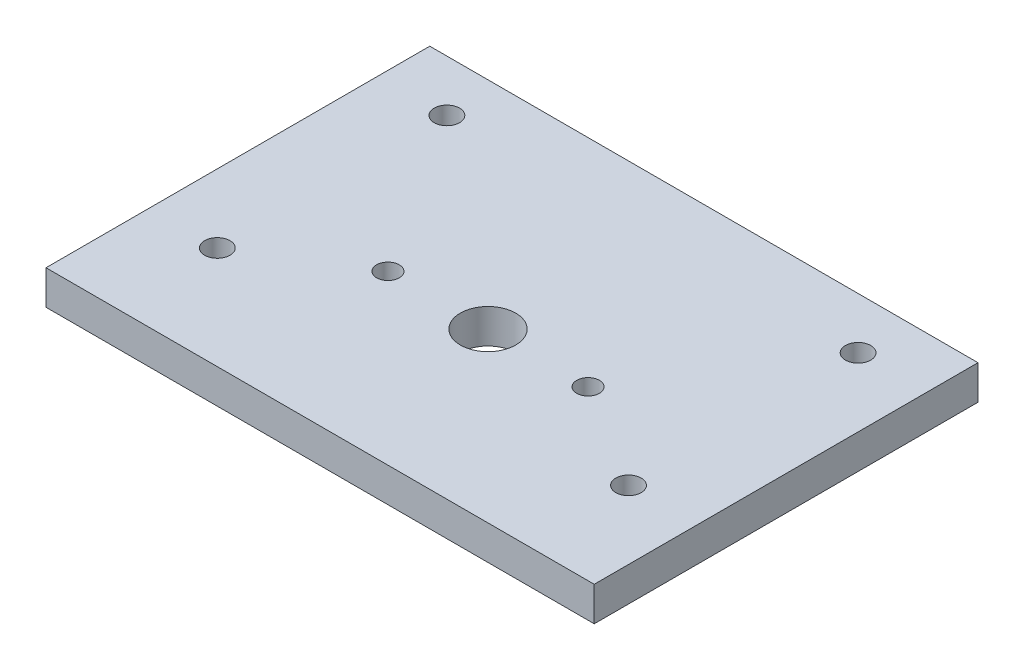
SolidWorks part; units mm, degrees
ref_plane "Front Plane" through (0, 0, 0) normal (0, 0, 1) x (1, 0, 0)
ref_plane "Top Plane" through (0, 0, 0) normal (0, 1, 0) x (1, 0, 0)
ref_plane "Right Plane" through (0, 0, 0) normal (1, 0, 0) x (0, 0, -1)
sketch "Sketch1" plane through (0, 0, 0) normal (0, 1, 0) x (1, 0, 0)
  line L1 (0, 0) -> (101.6, 0)
  line L2 (0, 0) -> (0, 71.12)
  line L3 (0, 71.12) -> (101.6, 71.12)
  line L4 (101.6, 0) -> (101.6, 71.12)
  dimension "D1" = 101.6
  dimension "D2" = 71.12
extrude "base" add sketch "Sketch1" along normal blind 6.35
hole_wizard "woodscrew clearance holes" positions "Sketch2" profile "Sketch3" hole size "#13" standard "ANSI Inch"
sketch "Sketch2" plane through (0, 6.35, 0) normal (0, 1, 0) x (1, 0, 0)
  line L2 (12.7, 61.595) -> (88.9, 61.595)
  line L3 (12.7, 61.595) -> (12.7, 19.05)
  line L4 (12.7, 19.05) -> (88.9, 19.05)
  line L5 (88.9, 61.595) -> (88.9, 19.05)
  line L6 (101.6, 71.12) -> (0, 71.12) construction
  line L7 (101.6, 0) -> (101.6, 71.12) construction
  line L8 (0, 71.12) -> (0, 0) construction
  line L9 (0, 0) -> (101.6, 0) construction
  point P0 (12.7, 61.595)
  point P2 (88.9, 61.595)
  point P4 (88.9, 19.05)
  point P6 (12.7, 19.05)
  dimension "D1" = 9.525
  dimension "D2" = 12.7
  dimension "D3" = 12.7
  dimension "D4" = 19.05
sketch "Sketch3" plane through (12.7, 6.35, -61.595) normal (1, 0, 0) x (0, 0, 1)
  line L0 (0, 0) -> (0, 7.7617)
  line L1 (0, 7.7617) -> (2.3495, 6.35)
  line L2 (2.3495, 6.35) -> (2.3495, 0)
  line L5 (2.3495, 0) -> (0, 0)
  line L10 (0, 7.7617) -> (-2.3495, 6.35) construction
  line L11 (0, -6.35) -> (0, 107.95) construction
  dimension "Hole Dia." = 4.699
  dimension "Hole Depth" = 6.35
  dimension "Drill Angle" = 118
hole_wizard "shaft clearance hole" positions "Sketch4" profile "Sketch5" hole size "Y" standard "ANSI Inch"
sketch "Sketch4" plane through (0, 6.35, 0) normal (0, 1, 0) x (1, 0, 0)
  line L0 (101.6, 0) -> (101.6, 71.12) construction
  line L1 (101.6, 71.12) -> (0, 71.12) construction
  point P0 (50.8, 31.115)
  dimension "D1" = 50.8
  dimension "D2" = 40.005
sketch "Sketch5" plane through (50.8, 6.35, -31.115) normal (1, 0, 0) x (0, 0, 1)
  line L0 (0, 0) -> (0, 9.4329)
  line L1 (0, 9.4329) -> (5.1308, 6.35)
  line L2 (5.1308, 6.35) -> (5.1308, 0)
  line L5 (5.1308, 0) -> (0, 0)
  line L10 (0, 9.4329) -> (-5.1308, 6.35) construction
  line L11 (0, -6.35) -> (0, 107.95) construction
  dimension "Hole Dia." = 10.2616
  dimension "Hole Depth" = 6.35
  dimension "Drill Angle" = 118
hole_wizard "M5x0.8 Tapped Hole1" positions "Sketch6" profile "Sketch7" tap size "M5x0.8" standard "ANSI Metric" end condition through all
sketch "Sketch6" plane through (0, 6.35, 0) normal (0, 1, 0) x (1, 0, 0)
  line L0 (32.258, 31.115) -> (69.342, 31.115)
  line L2 (50.8, 31.115) -> (50.8, 71.12)
  line L3 (101.6, 71.12) -> (0, 71.12) construction
  circle A0 centre (50.8, 31.115) radius 5.1308 construction
  point P0 (32.258, 31.115)
  point P2 (69.342, 31.115)
  dimension "D1" = 37.084
sketch "Sketch7" plane through (32.258, 6.35, -31.115) normal (1, 0, 0) x (0, 0, 1)
  line L0 (0, 0) -> (0, 6.35)
  line L1 (0, 6.35) -> (2.1, 6.35)
  line L2 (2.1, 6.35) -> (2.1, 0)
  line L5 (2.1, 0) -> (0, 0)
  line L11 (0, -6.35) -> (0, 107.95) construction
  dimension "Thru Tap Drill Dia." = 4.2
  dimension "Thru Tap Drill Depth" = 6.35
cosmetic thread "Hole Thread1" parameters "D2"=5
cosmetic thread "Hole Thread2" parameters "D2"=5
equation "\"D1@Sketch2\"=0.375in"
equation "\"D2@Sketch2\"=0.5in"
equation "\"D3@Sketch2\"=.5in"
equation "\"D4@Sketch2\"=0.75in"
equation "\"D1@Sketch4\"=2in"
